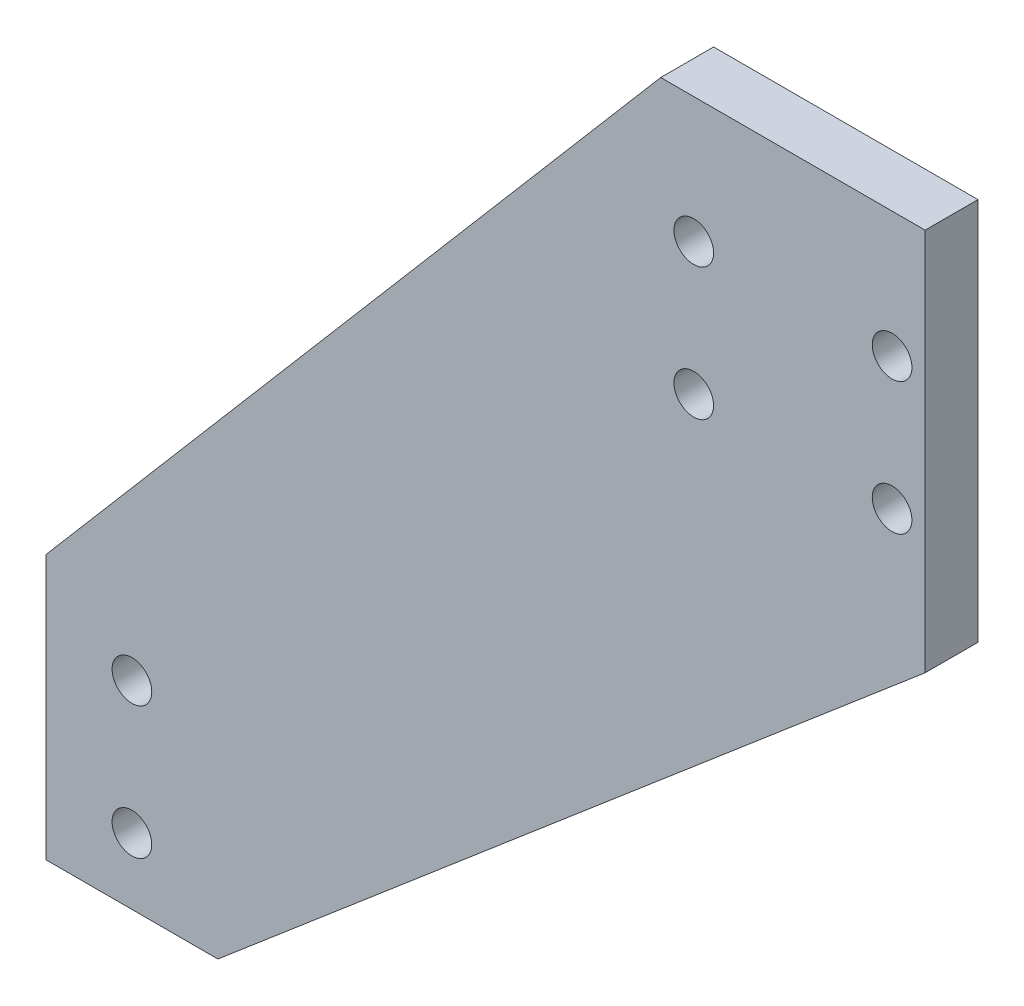
SolidWorks part; units mm, degrees
ref_plane "前视基准面" through (0, 0, 0) normal (0, 0, 1) x (1, 0, 0)
ref_plane "上视基准面" through (0, 0, 0) normal (0, 1, 0) x (1, 0, 0)
ref_plane "右视基准面" through (0, 0, 0) normal (1, 0, 0) x (0, 0, -1)
other "Configuration Table"
sketch "草图1" plane through (0, 0, 0) normal (0, 0, 1) x (1, 0, 0)
  line L0 (0, 0) -> (13, 0)
  line L1 (13, 0) -> (66.5, 45.5)
  line L2 (66.5, 45.5) -> (66.5, 74.5)
  line L3 (66.5, 74.5) -> (46.5, 74.5)
  line L4 (46.5, 74.5) -> (0, 20)
  line L5 (0, 20) -> (0, 0)
  line L6 (0, 20) -> (13, 20) construction
  line L7 (13, 20) -> (13, 0) construction
  line L8 (46.5, 74.5) -> (46.5, 45.5) construction
  line L9 (46.5, 45.5) -> (66.5, 45.5) construction
  line L10 (0, 10) -> (13, 10) construction
  line L11 (6.5, 10) -> (6.5, 15) construction
  line L12 (46.5, 60) -> (66.5, 60) construction
  line L13 (56.5, 60) -> (56.5, 74.5) construction
  circle A0 centre (6.5, 15) radius 1.5
  circle A1 centre (6.5, 5) radius 1.5
  circle A2 centre (49, 55) radius 1.5
  circle A3 centre (64, 55) radius 1.5
  circle A4 centre (49, 65) radius 1.5
  circle A5 centre (64, 65) radius 1.5
  dimension "D1" = 3
  dimension "D2" = 3
  dimension "D5" = 10
  dimension "D6" = 15
  dimension "D9" = 10
  dimension "D3" = 20
  dimension "D4" = 29
  dimension "D7" = 20
  dimension "D8" = 13
  dimension "D10" = 50
  dimension "D11" = 50
extrude "凸台-拉伸1" add sketch "草图1" along normal blind 4
